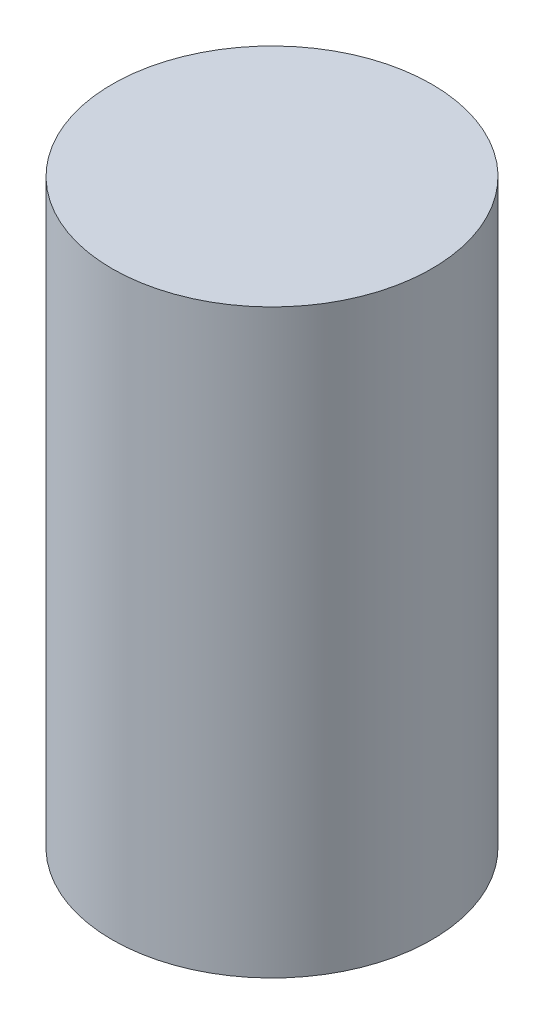
SolidWorks part; units mm, degrees
ref_plane "Спереди" through (0, 0, 0) normal (0, 0, 1) x (1, 0, 0)
ref_plane "Сверху" through (0, 0, 0) normal (0, 1, 0) x (1, 0, 0)
ref_plane "Справа" through (0, 0, 0) normal (1, 0, 0) x (0, 0, -1)
sketch "Эскиз1" plane through (0, 0, 0) normal (0, 1, 0) x (1, 0, 0)
  circle A0 centre (0, 0) radius 33
extrude "Бобышка-Вытянуть1" add sketch "Эскиз1" along normal blind 120
